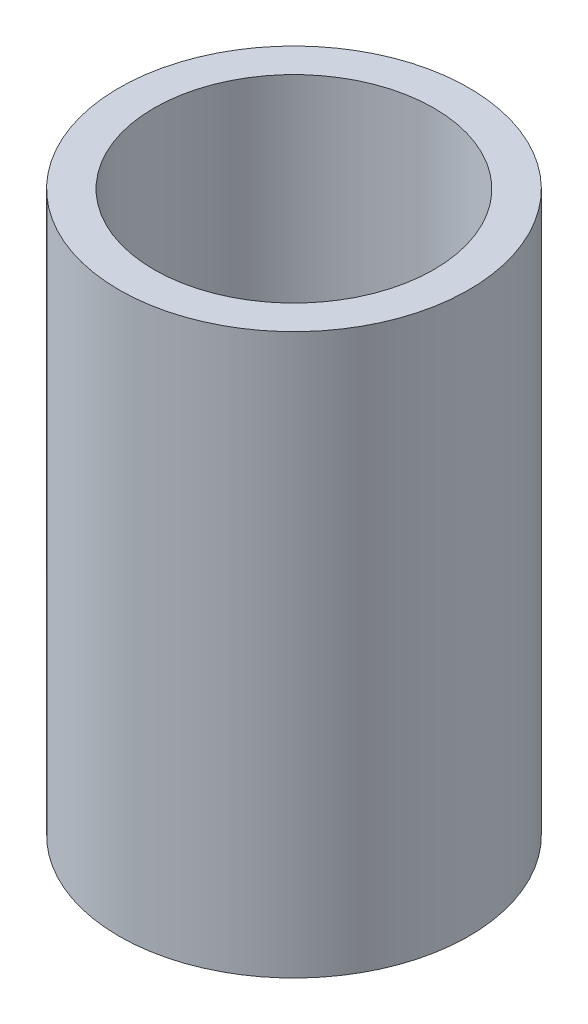
SolidWorks part; units mm, degrees
material "Сталь 20 ГОСТ 1050-88"
ref_plane "Спереди" through (0, 0, 0) normal (0, 0, 1) x (1, 0, 0)
ref_plane "Сверху" through (0, 0, 0) normal (0, 1, 0) x (1, 0, 0)
ref_plane "Справа" through (0, 0, 0) normal (1, 0, 0) x (0, 0, -1)
sketch "Эскиз1" plane through (0, 0, 0) normal (0, 1, 0) x (1, 0, 0)
  circle A0 centre (0, 0) radius 5
  circle A1 centre (0, 0) radius 4
  dimension "D1" = 10
  dimension "D2" = 8
extrude "Бобышка-Вытянуть1" add sketch "Эскиз1" along normal blind 16
